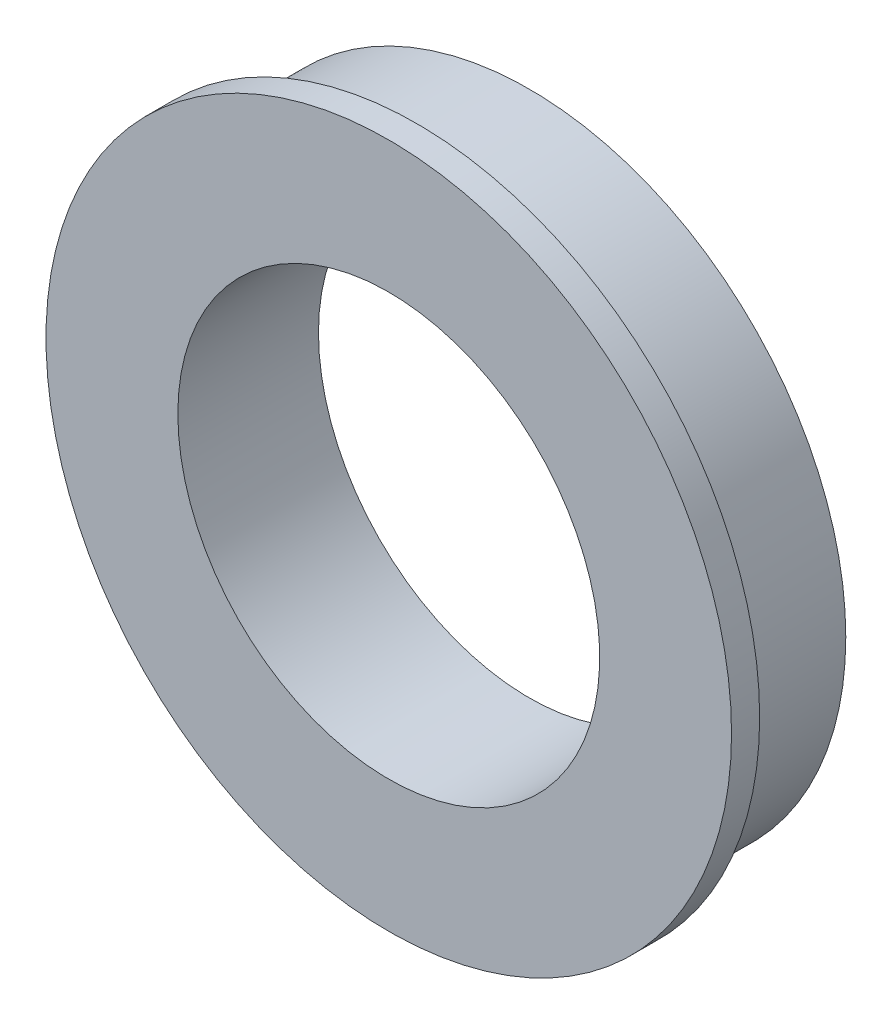
SolidWorks part; units mm, degrees
material "GCr15"
ref_plane "前视基准面" through (0, 0, 0) normal (0, 0, 1) x (1, 0, 0)
ref_plane "上视基准面" through (0, 0, 0) normal (0, 1, 0) x (1, 0, 0)
ref_plane "右视基准面" through (0, 0, 0) normal (1, 0, 0) x (0, 0, -1)
sketch "草图1" plane through (0, 0, 0) normal (0, 0, 1) x (1, 0, 0)
  circle A1 centre (0, 0) radius 9
  dimension "D2" = 18
extrude "凸台-拉伸1" add sketch "草图1" along normal blind 4
sketch "草图2" plane through (0, 0, 4) normal (0, 0, 1) x (1, 0, 0)
  circle A0 centre (0, 0) radius 9.75
  dimension "D1" = 19.5
extrude "凸台-拉伸2" add sketch "草图2" against normal blind 0.8
sketch "草图3" plane through (0, 0, 0) normal (0, 0, -1) x (-1, 0, 0)
  circle A0 centre (0, 0) radius 6
  dimension "D1" = 12
extrude "切除-拉伸1" cut sketch "草图3" against normal through all
move or copy body "实体-移动/复制1" [suppressed] bodies to move or copy 108
